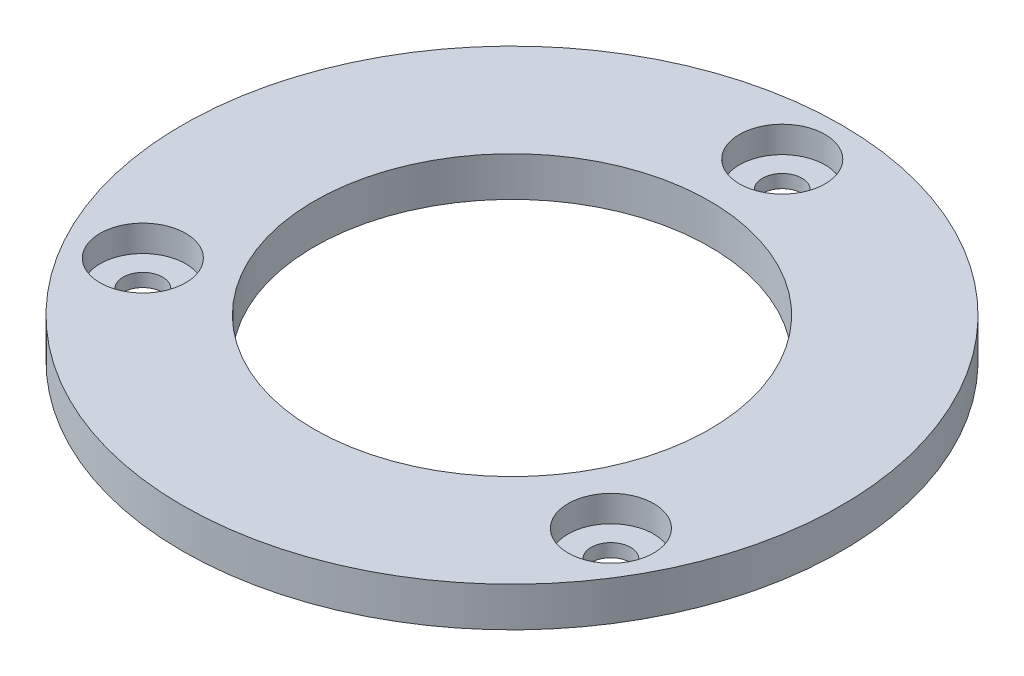
SolidWorks part; units mm, degrees
ref_plane "Front Plane" through (0, 0, 0) normal (0, 0, 1) x (1, 0, 0)
ref_plane "Top Plane" through (0, 0, 0) normal (0, 1, 0) x (1, 0, 0)
ref_plane "Right Plane" through (0, 0, 0) normal (1, 0, 0) x (0, 0, -1)
sketch "Sketch1" plane through (0, 0, 0) normal (0, 1, 0) x (1, 0, 0)
  line L0 (0, 20.5) -> (0, 0) construction
  line L1 (0, 0) -> (0, 20.5) construction
  circle A0 centre (0, 0) radius 25
  circle A1 centre (0, 20.5) radius 1.5
  circle A2 centre (17.7535, -10.25) radius 1.5
  circle A3 centre (-17.7535, -10.25) radius 1.5
  circle A4 centre (0, 0) radius 15
  dimension "D1" = 20.5
  dimension "D2" = 3
  dimension "D3" = 50
  dimension "D5" = 30
  dimension "D4" = 3
extrude "Boss-Extrude1" add sketch "Sketch1" along normal blind 3
sketch "Sketch2" plane through (0, 3, 0) normal (0, 1, 0) x (1, 0, 0)
  circle A0 centre (0, 20.5) radius 3.25
  circle A1 centre (17.7535, -10.25) radius 3.25
  circle A2 centre (-17.7535, -10.25) radius 3.25
  dimension "D1" = 6.5
extrude "Cut-Extrude1" cut sketch "Sketch2" against normal blind 2
